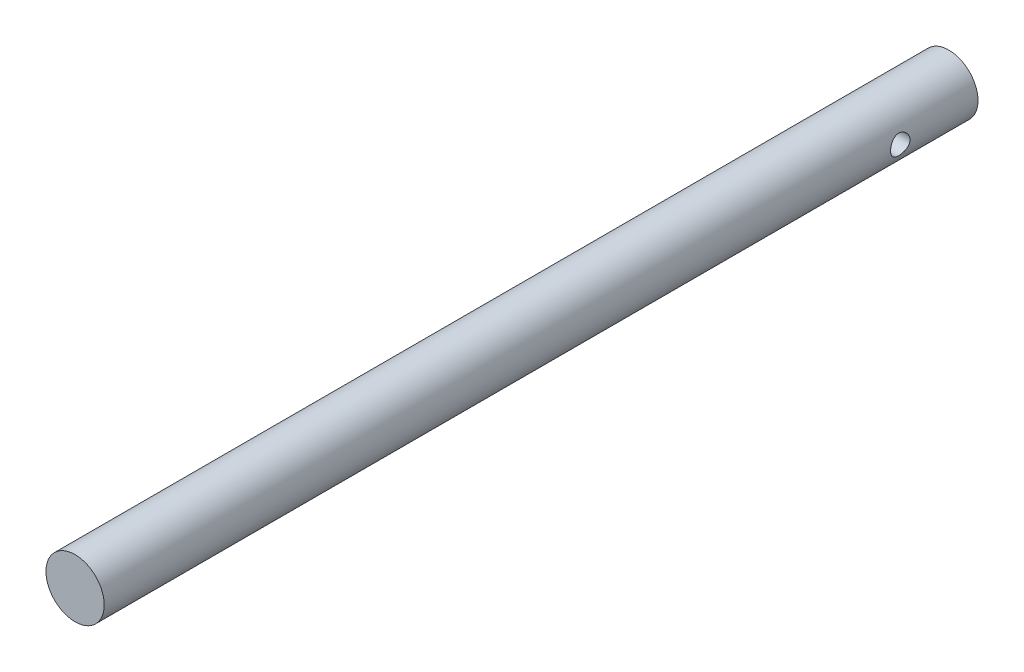
SolidWorks part; units mm, degrees
ref_plane "Ön Düzlem" through (0, 0, 0) normal (0, 0, 1) x (1, 0, 0)
ref_plane "Üst Düzlem" through (0, 0, 0) normal (0, 1, 0) x (1, 0, 0)
ref_plane "Sağ Düzlem" through (0, 0, 0) normal (1, 0, 0) x (0, 0, -1)
sketch "Çizim1" plane through (0, 0, 0) normal (0, 0, 1) x (1, 0, 0)
  circle A0 centre (0, 0) radius 4.5
extrude "Yükseklik-Ekstrüzyon1" add sketch "Çizim1" along normal blind 15
sketch "Çizim2" plane through (0, 0, 0) normal (1, 0, 0) x (0, 0, -1)
  line L0 (-15, 4.5) -> (-15, -4.5) construction
  line L1 (0, 4.5) -> (-15, 4.5) construction
  line L2 (-15, 4.5) -> (-15, -4.5)
  line L3 (0, 4.5) -> (-15, 4.5)
  circle A0 centre (-12, 0) radius 1.5
  dimension "D2" = 3
extrude "Kes-Ekstrüzyon1" cut sketch "Çizim2" against normal up to next and the other way up to next contours A0
sketch "Çizim3" plane through (0, 0, 15) normal (0, 0, 1) x (1, 0, 0)
  circle A1 centre (0, 0) radius 4.5
  circle A2 centre (0, 0) radius 4.5
  dimension "D1" = 0
extrude "Yükseklik-Ekstrüzyon2" add sketch "Çizim3" along normal blind 120
